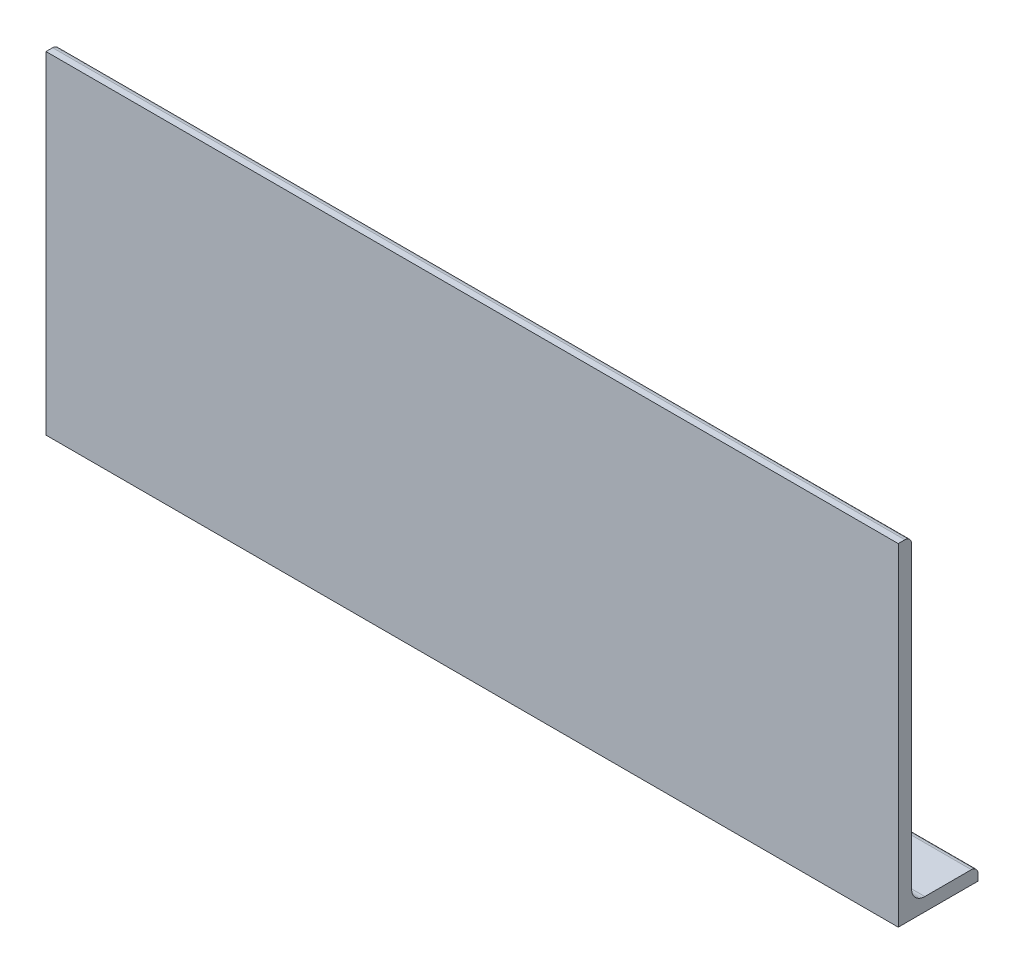
SolidWorks part; units mm, degrees
ref_plane "Front Plane" through (0, 0, 0) normal (0, 0, 1) x (1, 0, 0)
ref_plane "Top Plane" through (0, 0, 0) normal (0, 1, 0) x (1, 0, 0)
ref_plane "Right Plane" through (0, 0, 0) normal (1, 0, 0) x (0, 0, -1)
sketch "Sketch1" plane through (0, 0, 0) normal (1, 0, 0) x (0, 0, -1)
  line L0 (-127.6975, -39.2153) -> (-127.6975, -89.2153)
  line L1 (-127.6975, -89.2153) -> (-115.6975, -89.2153)
  line L2 (-115.6975, -89.2153) -> (-115.6975, -87.2153)
  line L3 (-115.6975, -87.2153) -> (-125.6975, -87.2153)
  line L4 (-125.6975, -87.2153) -> (-125.6975, -39.2153)
  line L5 (-125.6975, -39.2153) -> (-127.6975, -39.2153)
  dimension "D1" = 2
  dimension "D2" = 2
  dimension "D3" = 12
  dimension "D4" = 50
extrude "Boss-Extrude1" add sketch "Sketch1" along normal blind 128.27
fillet "Fillet1" radius 1 2 edges at (64.135, -87.2153, 115.6975) (64.135, -39.2153, 125.6975)
fillet "Fillet2" radius 2 1 edges at (64.135, -87.2153, 125.6975)
sketch "Sketch2" plane through (0, -87.2153, 0) normal (0, 1, 0) x (1, 0, 0)
  line L0 (0, -115.6975) -> (128.27, -115.6975) construction
  line L1 (0, -116.6975) -> (0, -123.6975) construction
  line L2 (128.27, -116.6975) -> (128.27, -123.6975) construction
  circle A0 centre (20, -120.1975) radius 1.6
  circle A1 centre (108.27, -120.1975) radius 1.6
  dimension "D1" = 3.2
  dimension "D2" = 3.2
  dimension "D3" = 4.5
  dimension "D4" = 4.5
  dimension "D5" = 20
  dimension "D6" = 20
extrude "Cut-Extrude1" cut sketch "Sketch2" against normal through all
